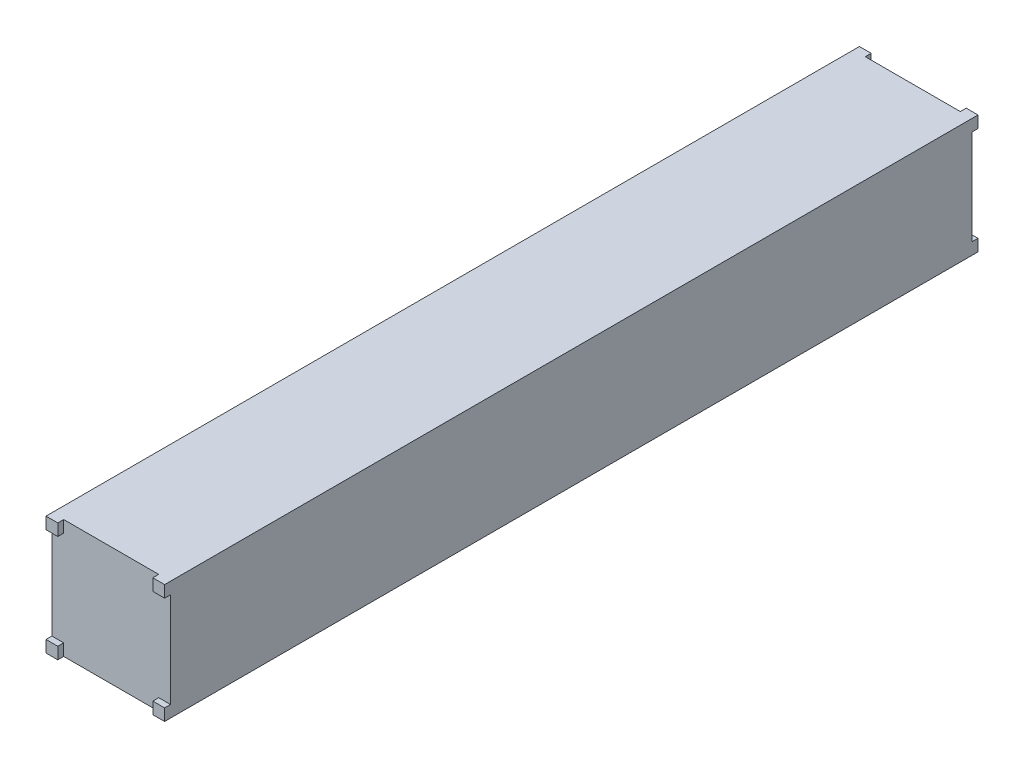
SolidWorks part; units mm, degrees
ref_plane "Front Plane" through (0, 0, 0) normal (0, 0, 1) x (1, 0, 0)
ref_plane "Top Plane" through (0, 0, 0) normal (0, 1, 0) x (1, 0, 0)
ref_plane "Right Plane" through (0, 0, 0) normal (1, 0, 0) x (0, 0, -1)
sketch "Sketch1" plane through (0, 0, 0) normal (0, 0, 1) x (1, 0, 0)
  line L1 (50.3, -50.3) -> (-50.3, -50.3)
  line L2 (50.3, -50.3) -> (50.3, 50.3)
  line L3 (50.3, 50.3) -> (-50.3, 50.3)
  line L4 (-50.3, -50.3) -> (-50.3, 50.3)
  line L5 (50.3, -50.3) -> (-50.3, 50.3) construction
  line L6 (50.3, 50.3) -> (-50.3, -50.3) construction
  point P0 (0, 0)
  dimension "D1" = 100.6
  dimension "D2" = 100.6
extrude "Boss-Extrude1" add sketch "Sketch1" along normal mid plane 680
sketch "Sketch2" plane through (0, 0, 340) normal (0, 0, 1) x (1, 0, 0)
  line L0 (0, 50.3) -> (0, -50.3) construction
  line L1 (-50.3, 50.3) -> (-40.3, 50.3)
  line L2 (-50.3, 50.3) -> (-50.3, 40.3)
  line L3 (-50.3, 40.3) -> (-40.3, 40.3)
  line L4 (-40.3, 50.3) -> (-40.3, 40.3)
  line L5 (50.3, 50.3) -> (-50.3, 50.3) construction
  line L6 (-50.3, -50.3) -> (50.3, -50.3) construction
  line L7 (50.3, 40.3) -> (40.3, 40.3)
  line L8 (40.3, 50.3) -> (40.3, 40.3)
  line L9 (50.3, 50.3) -> (40.3, 50.3)
  line L10 (50.3, 50.3) -> (50.3, 40.3)
  line L11 (-50.3, 0) -> (50.3, 0) construction
  line L12 (-50.3, 50.3) -> (-50.3, -50.3) construction
  line L13 (50.3, -50.3) -> (50.3, 50.3) construction
  line L14 (50.3, -50.3) -> (50.3, -40.3)
  line L15 (50.3, -50.3) -> (40.3, -50.3)
  line L16 (40.3, -50.3) -> (40.3, -40.3)
  line L17 (50.3, -40.3) -> (40.3, -40.3)
  line L18 (-50.3, -40.3) -> (-40.3, -40.3)
  line L19 (-40.3, -50.3) -> (-40.3, -40.3)
  line L20 (-50.3, -50.3) -> (-40.3, -50.3)
  line L21 (-50.3, -50.3) -> (-50.3, -40.3)
  dimension "D1" = 10
  dimension "D2" = 10
extrude "Boss-Extrude2" add sketch "Sketch2" along normal blind 5
sketch "Sketch3" plane through (0, 0, -340) normal (0, 0, -1) x (-1, 0, 0)
  line L0 (0, 50.3) -> (0, 0) construction
  line L1 (-50.3, 50.3) -> (-40.3, 50.3)
  line L2 (-50.3, 50.3) -> (-50.3, 40.3)
  line L3 (-50.3, 40.3) -> (-40.3, 40.3)
  line L4 (-40.3, 50.3) -> (-40.3, 40.3)
  line L5 (-50.3, 50.3) -> (50.3, 50.3) construction
  line L6 (0, 0) -> (50.3, 0) construction
  line L7 (50.3, 50.3) -> (50.3, -50.3) construction
  line L8 (50.3, 40.3) -> (40.3, 40.3)
  line L9 (40.3, 50.3) -> (40.3, 40.3)
  line L10 (50.3, 50.3) -> (40.3, 50.3)
  line L11 (50.3, 50.3) -> (50.3, 40.3)
  line L12 (50.3, -50.3) -> (50.3, -40.3)
  line L13 (50.3, -50.3) -> (40.3, -50.3)
  line L14 (40.3, -50.3) -> (40.3, -40.3)
  line L15 (50.3, -40.3) -> (40.3, -40.3)
  line L16 (-50.3, -40.3) -> (-40.3, -40.3)
  line L17 (-40.3, -50.3) -> (-40.3, -40.3)
  line L18 (-50.3, -50.3) -> (-40.3, -50.3)
  line L19 (-50.3, -50.3) -> (-50.3, -40.3)
  dimension "D1" = 10
  dimension "D2" = 10
extrude "Boss-Extrude3" add sketch "Sketch3" along normal blind 5
